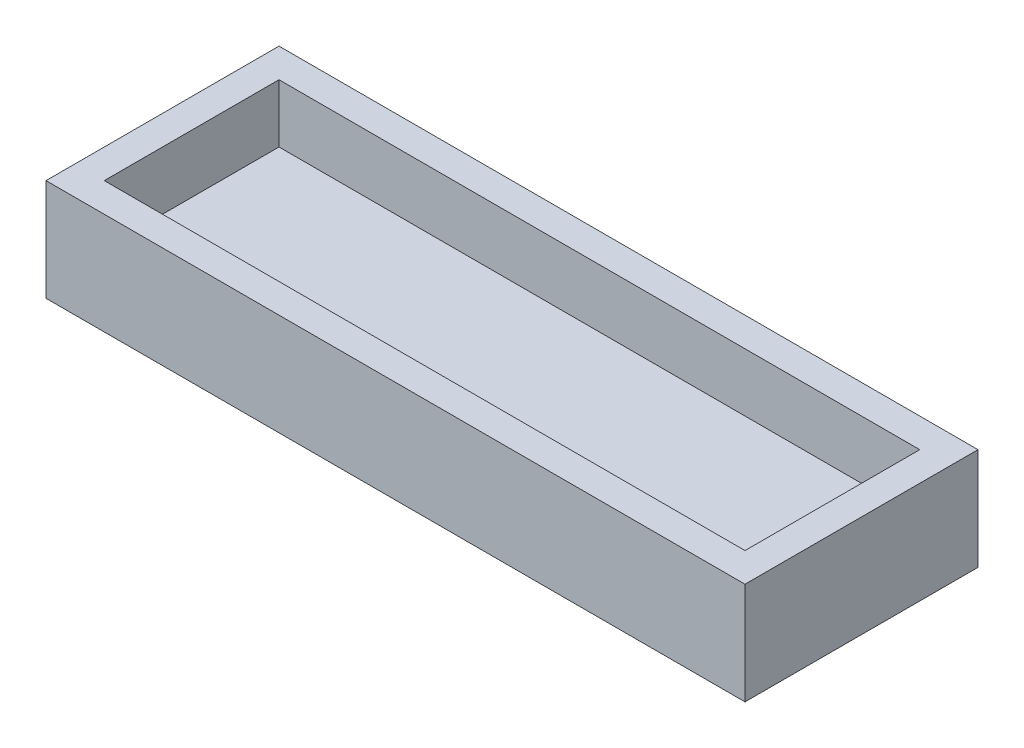
SolidWorks part; units mm, degrees
ref_plane "Front Plane" through (0, 0, 0) normal (0, 0, 1) x (1, 0, 0)
ref_plane "Top Plane" through (0, 0, 0) normal (0, 1, 0) x (1, 0, 0)
ref_plane "Right Plane" through (0, 0, 0) normal (1, 0, 0) x (0, 0, -1)
sketch "Sketch1" plane through (0, 0, 0) normal (0, 1, 0) x (1, 0, 0)
  line L1 (-22, 6) -> (22, 6)
  line L2 (-22, 6) -> (-22, -6)
  line L3 (-22, -6) -> (22, -6)
  line L4 (22, 6) -> (22, -6)
  line L5 (-22, 6) -> (22, -6) construction
  line L6 (-22, -6) -> (22, 6) construction
  point P0 (0, 0)
extrude "Boss-Extrude1" add sketch "Sketch1" along normal blind 3
sketch "Sketch2" plane through (0, 0, 0) normal (0, -1, 0) x (1, 0, 0)
  line L0 (24, -8) -> (24, 8)
  line L17 (24, 8) -> (-24, 8)
  line L18 (22, -6) -> (-22, -6)
  line L19 (22, -6) -> (22, 6)
  line L20 (22, 6) -> (-22, 6)
  line L21 (-22, -6) -> (-22, 6)
  line L22 (22, -6) -> (-22, 6) construction
  line L23 (22, 6) -> (-22, -6) construction
  line L24 (-24, -8) -> (-24, 8)
  line L25 (24, -8) -> (-24, -8)
  point P0 (0, 0)
  dimension "D1" = 2
extrude "Boss-Extrude2" add sketch "Sketch2" against normal offset from surface (7 mm away) 4 up to face at (0, 3, 0) offset beyond the face yes
